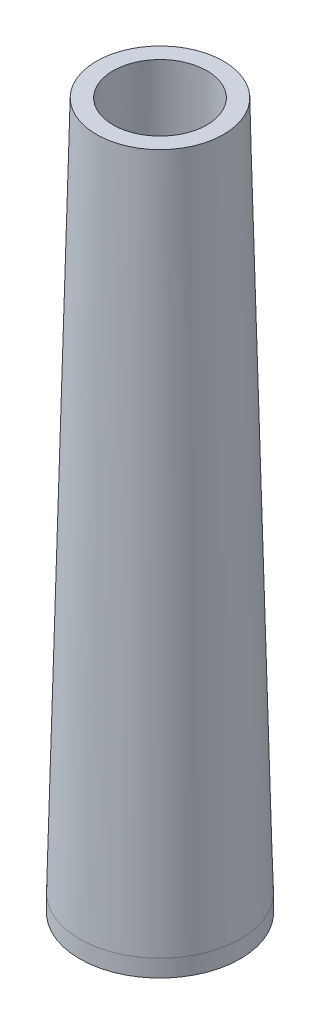
SolidWorks part; units mm, degrees
ref_plane "Alzado" through (0, 0, 0) normal (0, 0, 1) x (1, 0, 0)
ref_plane "Planta" through (0, 0, 0) normal (0, 1, 0) x (1, 0, 0)
ref_plane "Vista lateral" through (0, 0, 0) normal (1, 0, 0) x (0, 0, -1)
sketch "Croquis1" plane through (0, 0, 0) normal (0, 1, 0) x (1, 0, 0)
  circle A0 centre (0, 0) radius 14
  dimension "D1" = 28
extrude "Saliente-Extruir1" add sketch "Croquis1" along normal blind 3
sketch "Croquis2" plane through (0, 3, 0) normal (0, 1, 0) x (1, 0, 0)
  circle A0 centre (0, 0) radius 11.075
  dimension "D1" = 22.15
extrude "Saliente-Extruir2" add sketch "Croquis2" along normal blind 120
sketch "Croquis3" plane through (0, 123, 0) normal (0, 1, 0) x (1, 0, 0)
  circle A0 centre (0, 0) radius 7.525
  circle A1 centre (0, 0) radius 11.075 construction
  dimension "D1" = 3.55
sketch "Croquis4" plane through (0, 0, 0) normal (0, 0, 1) x (1, 0, 0)
  line L0 (0, 0) -> (0, 125.2226) construction
  line L1 (14, 3) -> (11.075, 3)
  line L2 (11.075, 3) -> (11.075, 123)
  line L3 (11.075, 123) -> (14, 3)
revolve "Revolución1" add sketch "Croquis4" angle 360 about L0
sketch "Croquis10" plane through (0, 123, 0) normal (0, 1, 0) x (1, 0, 0)
  circle A1 centre (0, 0) radius 9
extrude "Cortar-Extruir1" cut sketch "Croquis10" against normal through all
sketch "Croquis11" plane through (0, 0, 0) normal (0, 0, 1) x (1, 0, 0)
  line L0 (0, 123) -> (0, 105) construction
  line L1 (9, 123) -> (-9, 123) construction
  line L2 (9, 123) -> (9, 105)
  line L3 (11.075, 123) -> (-11.075, 123) construction
  line L4 (9, 105) -> (8.1826, 123)
  line L5 (8.1826, 123) -> (9, 123)
  dimension "D1" = 18
  dimension "D2" = 9
  dimension "D3" = 2.6
revolve "Revolución2" add sketch "Croquis11" angle 360 about L0
